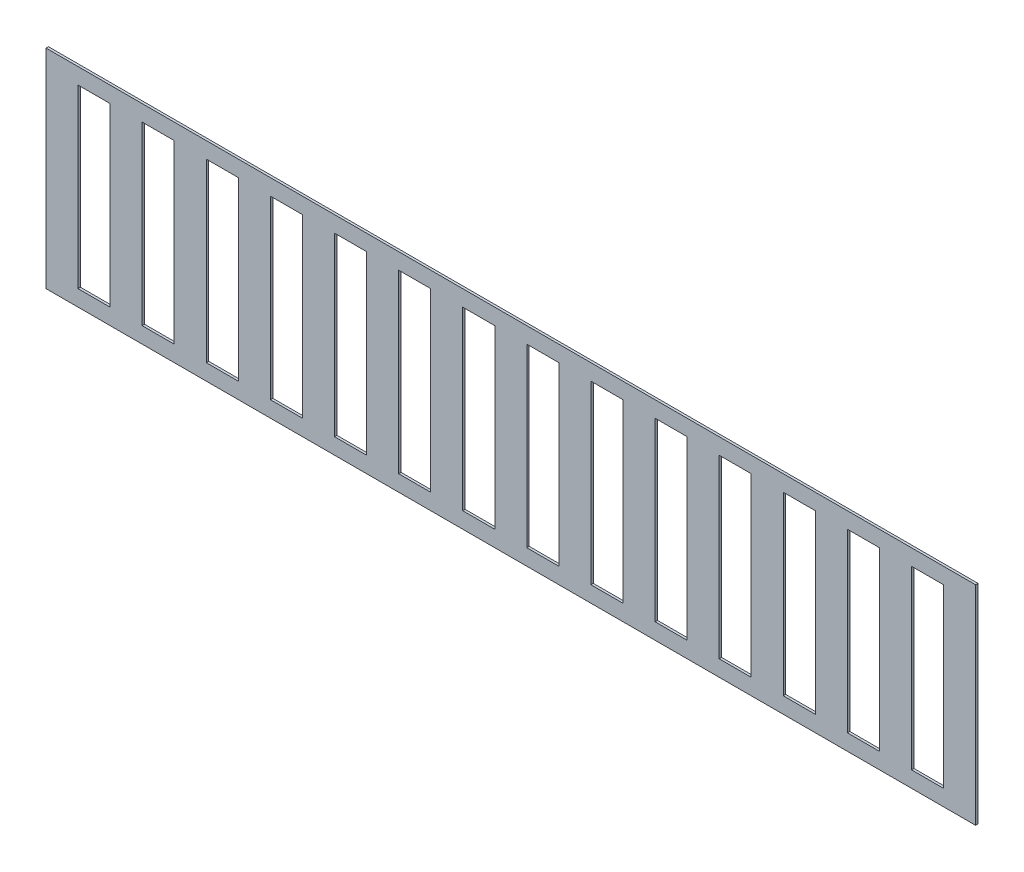
SolidWorks part; units mm, degrees
ref_plane "Front Plane" through (0, 0, 0) normal (0, 0, 1) x (1, 0, 0)
ref_plane "Top Plane" through (0, 0, 0) normal (0, 1, 0) x (1, 0, 0)
ref_plane "Right Plane" through (0, 0, 0) normal (1, 0, 0) x (0, 0, -1)
other "Configuration Table"
sketch "Sketch1" plane through (0, 0, 0) normal (0, 0, 1) x (1, 0, 0)
  line L1 (60, 40) -> (640, 40)
  line L2 (60, 40) -> (60, 170)
  line L3 (60, 170) -> (640, 170)
  line L4 (640, 40) -> (640, 170)
extrude "TOPPING_plint_izgara_paneli_1" add sketch "Sketch1" along normal blind 1.5 from offset 18.5 separate body
sketch "Sketch2" plane through (0, 0, 0) normal (0, 0, 1) x (1, 0, 0)
  line L1 (80, 50) -> (100, 50)
  line L2 (80, 50) -> (80, 160)
  line L3 (80, 160) -> (100, 160)
  line L4 (100, 50) -> (100, 160)
extrude "TOPPING_plint_izgara_paneli_2" cut sketch "Sketch2" along normal blind 4 from offset 17
sketch "Sketch3" plane through (0, 0, 0) normal (0, 0, 1) x (1, 0, 0)
  line L1 (120, 50) -> (140, 50)
  line L2 (120, 50) -> (120, 160)
  line L3 (120, 160) -> (140, 160)
  line L4 (140, 50) -> (140, 160)
extrude "TOPPING_plint_izgara_paneli_3" cut sketch "Sketch3" along normal blind 4 from offset 17
sketch "Sketch4" plane through (0, 0, 0) normal (0, 0, 1) x (1, 0, 0)
  line L1 (160, 50) -> (180, 50)
  line L2 (160, 50) -> (160, 160)
  line L3 (160, 160) -> (180, 160)
  line L4 (180, 50) -> (180, 160)
extrude "TOPPING_plint_izgara_paneli_4" cut sketch "Sketch4" along normal blind 4 from offset 17
sketch "Sketch5" plane through (0, 0, 0) normal (0, 0, 1) x (1, 0, 0)
  line L1 (200, 50) -> (220, 50)
  line L2 (200, 50) -> (200, 160)
  line L3 (200, 160) -> (220, 160)
  line L4 (220, 50) -> (220, 160)
extrude "TOPPING_plint_izgara_paneli_5" cut sketch "Sketch5" along normal blind 4 from offset 17
sketch "Sketch6" plane through (0, 0, 0) normal (0, 0, 1) x (1, 0, 0)
  line L1 (240, 50) -> (260, 50)
  line L2 (240, 50) -> (240, 160)
  line L3 (240, 160) -> (260, 160)
  line L4 (260, 50) -> (260, 160)
extrude "TOPPING_plint_izgara_paneli_6" cut sketch "Sketch6" along normal blind 4 from offset 17
sketch "Sketch7" plane through (0, 0, 0) normal (0, 0, 1) x (1, 0, 0)
  line L1 (280, 50) -> (300, 50)
  line L2 (280, 50) -> (280, 160)
  line L3 (280, 160) -> (300, 160)
  line L4 (300, 50) -> (300, 160)
extrude "TOPPING_plint_izgara_paneli_7" cut sketch "Sketch7" along normal blind 4 from offset 17
sketch "Sketch8" plane through (0, 0, 0) normal (0, 0, 1) x (1, 0, 0)
  line L1 (320, 50) -> (340, 50)
  line L2 (320, 50) -> (320, 160)
  line L3 (320, 160) -> (340, 160)
  line L4 (340, 50) -> (340, 160)
extrude "TOPPING_plint_izgara_paneli_8" cut sketch "Sketch8" along normal blind 4 from offset 17
sketch "Sketch9" plane through (0, 0, 0) normal (0, 0, 1) x (1, 0, 0)
  line L1 (360, 50) -> (380, 50)
  line L2 (360, 50) -> (360, 160)
  line L3 (360, 160) -> (380, 160)
  line L4 (380, 50) -> (380, 160)
extrude "TOPPING_plint_izgara_paneli_9" cut sketch "Sketch9" along normal blind 4 from offset 17
sketch "Sketch10" plane through (0, 0, 0) normal (0, 0, 1) x (1, 0, 0)
  line L1 (400, 50) -> (420, 50)
  line L2 (400, 50) -> (400, 160)
  line L3 (400, 160) -> (420, 160)
  line L4 (420, 50) -> (420, 160)
extrude "TOPPING_plint_izgara_paneli_10" cut sketch "Sketch10" along normal blind 4 from offset 17
sketch "Sketch11" plane through (0, 0, 0) normal (0, 0, 1) x (1, 0, 0)
  line L1 (440, 50) -> (460, 50)
  line L2 (440, 50) -> (440, 160)
  line L3 (440, 160) -> (460, 160)
  line L4 (460, 50) -> (460, 160)
extrude "TOPPING_plint_izgara_paneli_11" cut sketch "Sketch11" along normal blind 4 from offset 17
sketch "Sketch12" plane through (0, 0, 0) normal (0, 0, 1) x (1, 0, 0)
  line L1 (480, 50) -> (500, 50)
  line L2 (480, 50) -> (480, 160)
  line L3 (480, 160) -> (500, 160)
  line L4 (500, 50) -> (500, 160)
extrude "TOPPING_plint_izgara_paneli_12" cut sketch "Sketch12" along normal blind 4 from offset 17
sketch "Sketch13" plane through (0, 0, 0) normal (0, 0, 1) x (1, 0, 0)
  line L1 (520, 50) -> (540, 50)
  line L2 (520, 50) -> (520, 160)
  line L3 (520, 160) -> (540, 160)
  line L4 (540, 50) -> (540, 160)
extrude "TOPPING_plint_izgara_paneli_13" cut sketch "Sketch13" along normal blind 4 from offset 17
sketch "Sketch14" plane through (0, 0, 0) normal (0, 0, 1) x (1, 0, 0)
  line L1 (560, 50) -> (580, 50)
  line L2 (560, 50) -> (560, 160)
  line L3 (560, 160) -> (580, 160)
  line L4 (580, 50) -> (580, 160)
extrude "TOPPING_plint_izgara_paneli_14" cut sketch "Sketch14" along normal blind 4 from offset 17
sketch "Sketch15" plane through (0, 0, 0) normal (0, 0, 1) x (1, 0, 0)
  line L1 (600, 50) -> (620, 50)
  line L2 (600, 50) -> (600, 160)
  line L3 (600, 160) -> (620, 160)
  line L4 (620, 50) -> (620, 160)
extrude "TOPPING_plint_izgara_paneli_15" cut sketch "Sketch15" along normal blind 4 from offset 17
